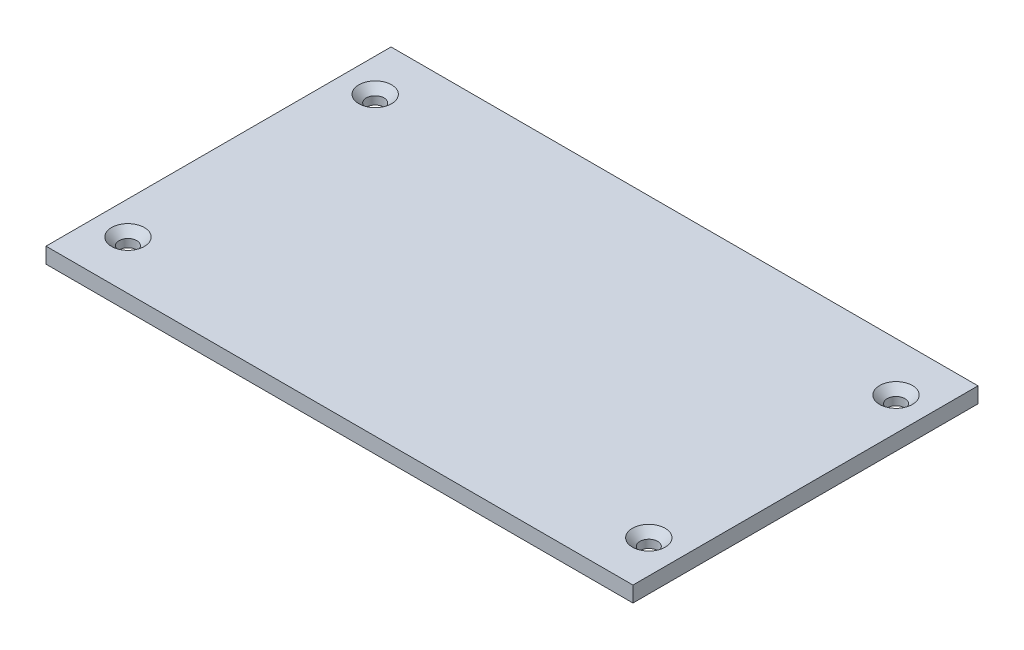
SolidWorks part; units mm, degrees
material "ABS"
ref_plane "Front Plane" through (0, 0, 0) normal (0, 0, 1) x (1, 0, 0)
ref_plane "Top Plane" through (0, 0, 0) normal (0, 1, 0) x (1, 0, 0)
ref_plane "Right Plane" through (0, 0, 0) normal (1, 0, 0) x (0, 0, -1)
sketch "Sketch1" plane through (0, 0, 0) normal (0, 1, 0) x (1, 0, 0)
  line L1 (-56.388, -33.147) -> (56.388, -33.147)
  line L2 (-56.388, -33.147) -> (-56.388, 33.147)
  line L3 (-56.388, 33.147) -> (56.388, 33.147)
  line L4 (56.388, -33.147) -> (56.388, 33.147)
  line L5 (-56.388, -33.147) -> (56.388, 33.147) construction
  line L6 (-56.388, 33.147) -> (56.388, -33.147) construction
  point P0 (0, 0)
  dimension "D1" = 66.294
  dimension "D2" = 112.776
extrude "Boss-Extrude1" add sketch "Sketch1" along normal blind 3 contours L2 L3 L4 L1
sketch "Sketch2" plane through (0, 3, 0) normal (0, 1, 0) x (1, 0, 0)
  line L0 (-56.388, 33.147) -> (56.388, 33.147) construction
  line L1 (-56.388, -33.147) -> (-56.388, 33.147) construction
  line L2 (56.388, -33.147) -> (56.388, 33.147) construction
  line L3 (-56.388, -33.147) -> (56.388, -33.147) construction
  point P0 (-50.038, 23.749)
  point P1 (-50.038, -23.749)
  point P2 (50.038, -23.749)
  point P3 (50.038, 23.749)
  dimension "D1" = 9.398
  dimension "D2" = 6.35
  dimension "D3" = 6.35
  dimension "D4" = 9.398
  dimension "D5" = 9.398
  dimension "D6" = 6.35
  dimension "D7" = 6.35
  dimension "D8" = 9.398
hole_wizard "CSK for M3 Countersunk Flat Head Screw1" positions "3DSketch1" profile "Sketch3" countersink size "M3" standard "ISO" end condition up to next
sketch3d "3DSketch1"
  point P0 (-50.038, 3, -23.749)
  point P3 (-50.038, 3, 23.749)
  point P6 (50.038, 3, 23.749)
  point P9 (50.038, 3, -23.749)
sketch "Sketch3" plane through (-50.038, 3, -23.749) normal (1, 0, 0) x (0, 0, 1)
  line L0 (0, 0) -> (0, 3)
  line L1 (0, 3) -> (1.7, 3)
  line L2 (1.7, 3) -> (1.7, 1.45)
  line L3 (1.7, 1.45) -> (3.15, 0)
  line L5 (3.15, 0) -> (0, 0)
  line L6 (-1.7, 1.45) -> (-3.15, 0) construction
  line L11 (0, -6.35) -> (0, 107.95) construction
  dimension "Thru Hole Dia." = 3.4
  dimension "Thru Hole Depth" = 3
  dimension "Near C'Sink Dia." = 6.3
  dimension "Near C'Sink Angle" = 90
